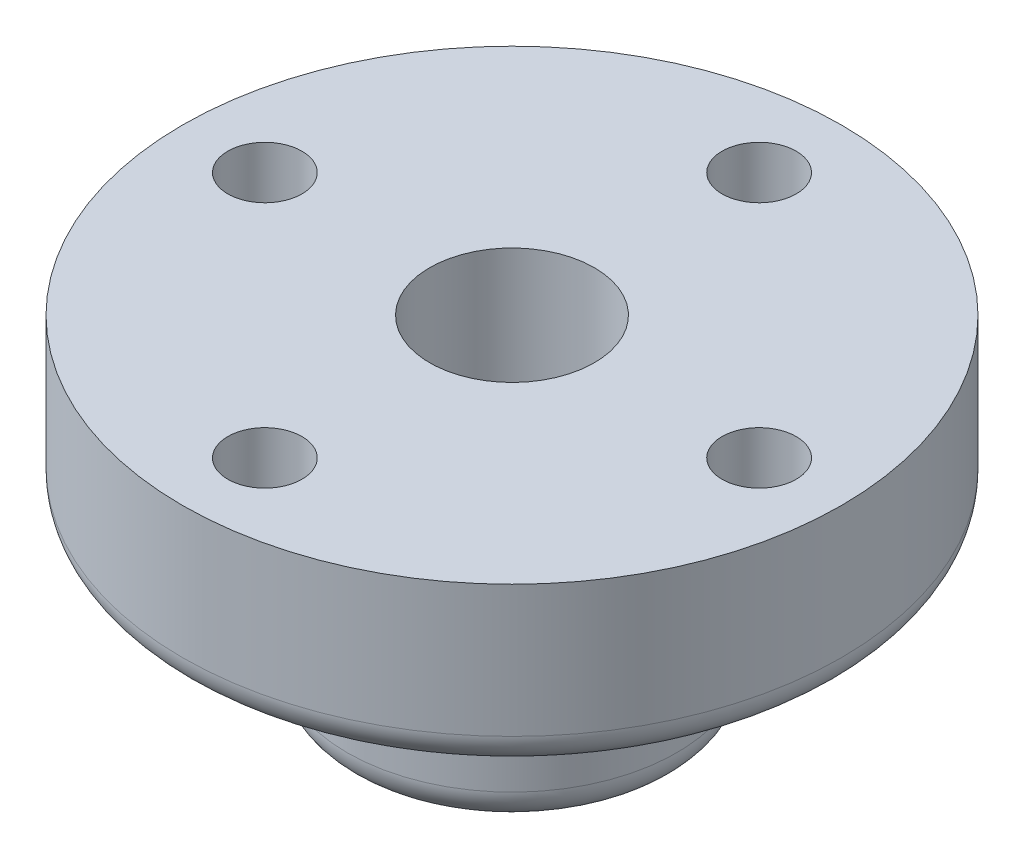
SolidWorks part; units mm, degrees
ref_plane "Front Plane" through (0, 0, 0) normal (0, 0, 1) x (1, 0, 0)
ref_plane "Top Plane" through (0, 0, 0) normal (0, 1, 0) x (1, 0, 0)
ref_plane "Right Plane" through (0, 0, 0) normal (1, 0, 0) x (0, 0, -1)
sketch "Sketch1" plane through (0, 0, 0) normal (0, 1, 0) x (1, 0, 0)
  circle A0 centre (0, 0) radius 254
  dimension "D1" = 508
extrude "Boss-Extrude1" add sketch "Sketch1" along normal blind 254
sketch "Sketch2" plane through (0, 254, 0) normal (0, 1, 0) x (1, 0, 0)
  circle A0 centre (0, 0) radius 508
  dimension "D1" = 1016
extrude "Boss-Extrude2" add sketch "Sketch2" along normal blind 254
sketch "Sketch3" plane through (0, 0, 0) normal (0, -1, 0) x (1, 0, 0)
  circle A0 centre (0, 0) radius 127
  dimension "D1" = 254
extrude "Cut-Extrude1" cut sketch "Sketch3" against normal through all
sketch "Sketch4" plane through (0, 254, 0) normal (0, -1, 0) x (1, 0, 0)
  line L0 (0, 629.3475) -> (0, -702.1292) construction
  line L1 (638.6069, 0) -> (-638.6069, 0) construction
  circle A0 centre (0, 0) radius 381 construction
  circle A1 centre (0, -381) radius 57.15
  circle A2 centre (381, 0) radius 57.15
  circle A3 centre (0, 381) radius 57.15
  circle A4 centre (-381, 0) radius 57.15
  dimension "D1" = 762
  dimension "D2" = 114.3
extrude "Cut-Extrude2" cut sketch "Sketch4" against normal through all
fillet "Fillet1" radius 50.8 3 edges at (0, 254, 508) (0, 254, 254) (0, 0, 254)
